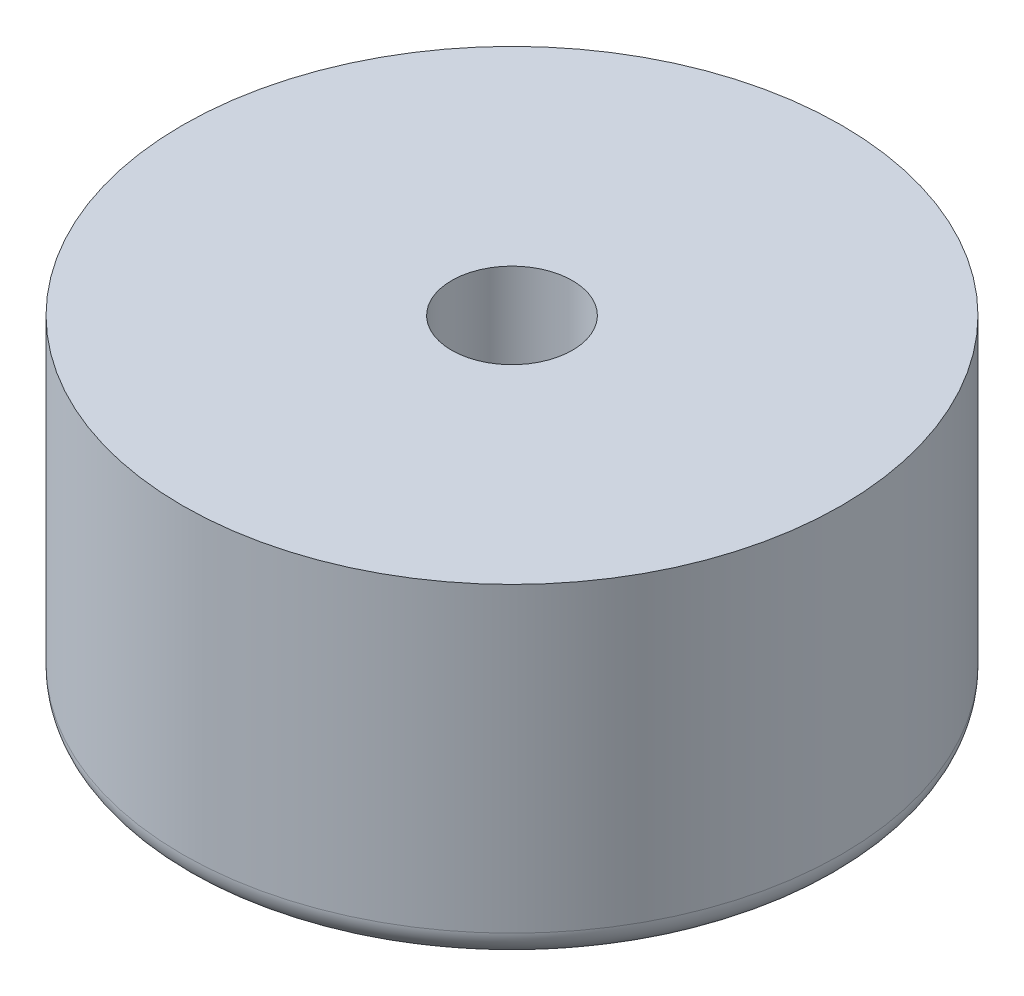
SolidWorks part; units mm, degrees
ref_plane "Front" through (0, 0, 0) normal (0, 0, 1) x (1, 0, 0)
ref_plane "Top" through (0, 0, 0) normal (0, 1, 0) x (1, 0, 0)
ref_plane "Right" through (0, 0, 0) normal (1, 0, 0) x (0, 0, -1)
sketch "Sketch1" plane through (0, 0, 0) normal (0, 1, 0) x (1, 0, 0)
  circle A0 centre (0, 0) radius 6
  dimension "D1" = 12
extrude "Boss-Extrude1" add sketch "Sketch1" along normal blind 6 contours A0
sketch "Sketch2" plane through (0, 6, 0) normal (0, 1, 0) x (1, 0, 0)
  circle A0 centre (0, 0) radius 1.1
extrude "Cut-Extrude1" cut sketch "Sketch2" against normal blind 4.3
fillet "Fillet1" radius 0.5 1 edges at (0, 0, 6)
